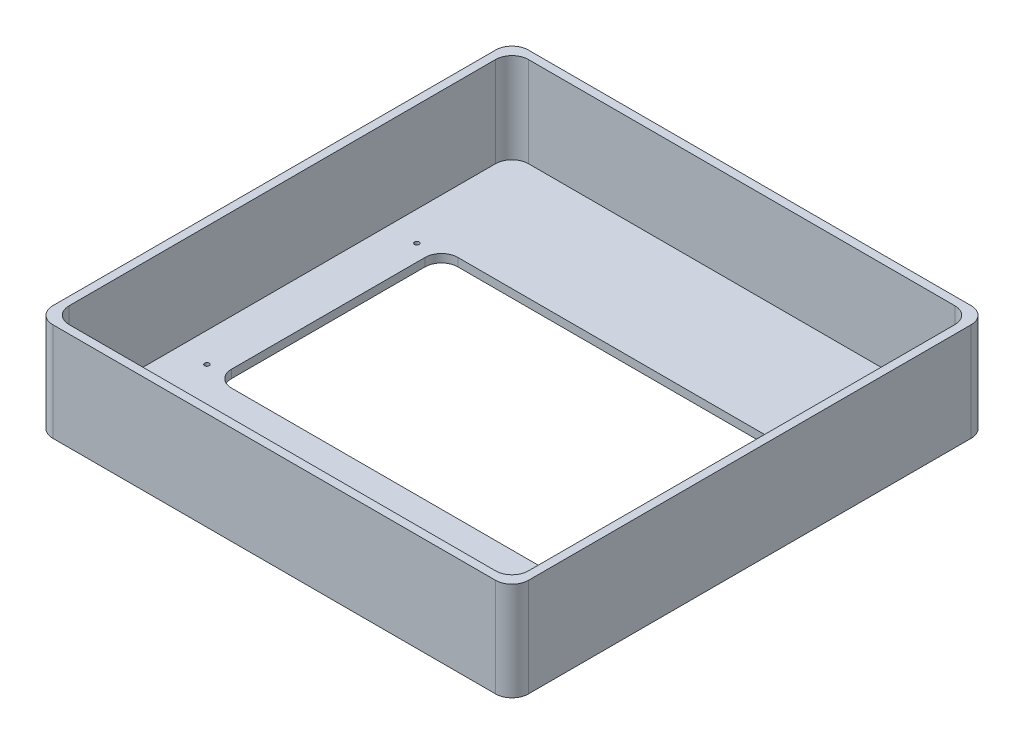
SolidWorks part; units mm, degrees
ref_plane "前视基准面" through (0, 0, 0) normal (0, 0, 1) x (1, 0, 0)
ref_plane "上视基准面" through (0, 0, 0) normal (0, 1, 0) x (1, 0, 0)
ref_plane "右视基准面" through (0, 0, 0) normal (1, 0, 0) x (0, 0, -1)
other "Configuration Table"
sketch "草图1" plane through (0, 0, 0) normal (0, 1, 0) x (1, 0, 0)
  line L1 (-130, -69) -> (130, -69) construction
  line L2 (-130, -69) -> (-130, 69) construction
  line L3 (-130, 69) -> (130, 69) construction
  line L4 (130, -69) -> (130, 69) construction
  line L5 (-130, -69) -> (130, 69) construction
  line L6 (-130, 69) -> (130, -69) construction
  line L7 (-145, -145) -> (145, -145)
  line L8 (-145, -145) -> (-145, 145)
  line L9 (-145, 145) -> (145, 145)
  line L10 (145, -145) -> (145, 145)
  line L11 (-145, -145) -> (145, 145) construction
  line L12 (-145, 145) -> (145, -145) construction
  point P1 (0, 0)
  point P6 (0, 0)
  dimension "D1" = 260
  dimension "D2" = 138
  dimension "D3" = 76
  dimension "D4" = 290
extrude "凸台-拉伸1" add sketch "草图1" along normal blind 60
sketch "草图2" plane through (0, 60, 0) normal (0, 1, 0) x (1, 0, 0)
  line L0 (140, -140) -> (140, 140)
  line L5 (140, 140) -> (-140, 140)
  line L6 (-140, 140) -> (-140, -140)
  line L7 (-140, -140) -> (140, -140)
  line L8 (145, -145) -> (145, 145)
  line L9 (145, 145) -> (-145, 145)
  line L10 (-145, 145) -> (-145, -145)
  line L11 (-145, -145) -> (145, -145)
  line L12 (145, -145) -> (145, 145) construction
  line L13 (145, 145) -> (-145, 145) construction
  line L14 (-145, 145) -> (-145, -145) construction
  line L15 (-145, -145) -> (145, -145) construction
  point P0 (0, 0)
  dimension "D1" = 0
  dimension "D2" = 5
extrude "切除-拉伸2" cut sketch "草图2" against normal offset from surface (55 mm away) 5 up to face at (0, 0, 0)
sketch "草图3" plane through (0, 5, 0) normal (0, 1, 0) x (1, 0, 0)
  line L4 (-140, -140) -> (140, -140)
  line L5 (140, -140) -> (140, 140)
  line L6 (140, 140) -> (-140, 140)
  line L7 (-140, 140) -> (-140, -140)
  line L9 (140, -69) -> (140, 69) construction
  line L20 (-112, -69) -> (112, -69)
  line L21 (-112, -69) -> (-112, 69)
  line L22 (-112, 69) -> (112, 69)
  line L23 (112, -69) -> (112, 69)
  line L24 (-112, -69) -> (112, 69) construction
  line L25 (-112, 69) -> (112, -69) construction
  point P10 (0, 0)
  dimension "D2" = 224
  dimension "D3" = 138
  dimension "D1" = 0
extrude "切除-拉伸3" cut sketch "草图3" against normal up to surface (5 mm away) up to face at (0, 0, 0)
sketch "草图4" plane through (0, 0, 0) normal (0, -1, 0) x (1, 0, 0)
  line L2 (0, 108.601) -> (0, -115.5528) construction
  line L3 (-130, -69) -> (130, -69) construction
  line L4 (-130, -69) -> (-130, 69) construction
  line L5 (-130, 69) -> (130, 69) construction
  line L6 (130, -69) -> (130, 69) construction
  line L7 (-130, -69) -> (130, 69) construction
  line L8 (-130, 69) -> (130, -69) construction
  line L9 (-174.0408, 0) -> (168.7186, 0) construction
  circle A0 centre (-122, 64) radius 1.4
  circle A1 centre (122, 64) radius 1.4
  circle A2 centre (122, -64) radius 1.4
  circle A3 centre (-122, -64) radius 1.4
  point P4 (0, 0)
  dimension "D3" = 2.8
  dimension "D5" = 244
  dimension "D1" = 260
  dimension "D2" = 138
  dimension "D4" = 128
extrude "切除-拉伸4" cut sketch "草图4" against normal up to surface (5 mm away) up to face at (0, 5, 0)
fillet "圆角1" radius 10 8 edges at (-145, 30, 145) (-140, 32.5, 140) (-145, 30, -145) (-140, 32.5, -140) (145, 30, -145) (140, 32.5, -140) (145, 30, 145) (140, 32.5, 140)
fillet "圆角2" radius 10 4 edges at (-112, 2.5, -69) (-112, 2.5, 69) (112, 2.5, 69) (112, 2.5, -69)
